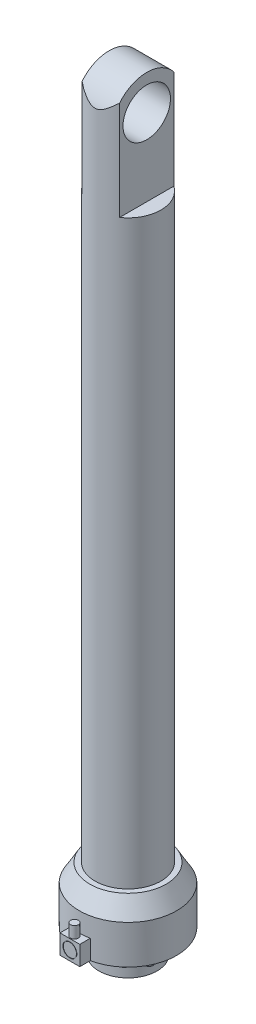
SolidWorks part; units mm, degrees
ref_plane "前基準面" through (0, 0, 0) normal (0, 0, 1) x (1, 0, 0)
ref_plane "上基準面" through (0, 0, 0) normal (0, 1, 0) x (1, 0, 0)
ref_plane "右基準面" through (0, 0, 0) normal (1, 0, 0) x (0, 0, -1)
sketch "草圖1" plane through (0, 0, 0) normal (0, 1, 0) x (1, 0, 0)
  circle A0 centre (0, 0) radius 8.5
  dimension "D1" = 17
extrude "填料-伸長1" add sketch "草圖1" along normal blind 150
sketch "草圖2" plane through (0, 150, 0) normal (0, 1, 0) x (1, 0, 0)
  line L1 (4.8323, -8.965) -> (-4.8323, -8.965)
  line L2 (4.8323, -8.965) -> (4.8323, 8.965)
  line L3 (4.8323, 8.965) -> (-4.8323, 8.965)
  line L4 (-4.8323, -8.965) -> (-4.8323, 8.965)
  line L5 (4.8323, -8.965) -> (-4.8323, 8.965) construction
  line L6 (4.8323, 8.965) -> (-4.8323, -8.965) construction
  point P0 (0, 0)
extrude "填料-伸長2" add sketch "草圖2" along normal blind 20
sketch "草圖3" plane through (4.8323, 0, 0) normal (1, 0, 0) x (0, 0, -1)
  line L0 (-8.965, 170) -> (8.965, 170) construction
  circle A0 centre (0, 170) radius 8.9308
extrude "填料-伸長3" add sketch "草圖3" against normal blind 9.7
sketch "草圖4" plane through (4.8323, 0, 0) normal (1, 0, 0) x (0, 0, -1)
  line L0 (0, -821.0692) -> (0, 49178.9308) construction
  line L1 (-1008.9308, 170) -> (48991.0692, 170) construction
  arc A0 (8.9308, 170) -> (-8.9308, 170) centre (0, 170) ccw construction
  circle A1 centre (0, 170) radius 6.1252
  point P6 (0, 178.9308)
extrude "除料-伸長1" cut sketch "草圖4" against normal blind 9.7
sketch "草圖5" plane through (0, 0, 0) normal (0, -1, 0) x (1, 0, 0)
  circle A0 centre (0, 0) radius 8.5
extrude "除料-伸長-薄件2" cut sketch "草圖5" against normal through all and the other way through all thin
sketch "草圖9" plane through (0, 0, 0) normal (1, 0, 0) x (0, 0, -1)
  line L0 (0, 0) -> (-9.8638, 0)
  line L1 (-9.8638, 0) -> (-12.56, -4.5997)
  line L2 (-12.56, -4.5997) -> (0, -4.5997)
  line L3 (0, -4.5997) -> (0, 0)
revolve "旋轉3" add sketch "草圖9" angle 360 about L3
sketch "草圖10" plane through (0, -4.5997, 0) normal (0, -1, 0) x (1, 0, 0)
  circle A0 centre (0, 0) radius 12.56
extrude "填料-伸長5" add sketch "草圖10" along normal blind 10
sketch "草圖11" plane through (0, -14.5997, 0) normal (0, -1, 0) x (1, 0, 0)
  line L0 (-1009.8752, 7.7611) -> (48990.1248, 7.7611) construction
  line L1 (-1011.7934, 4.3209) -> (48988.2066, 4.3209) construction
  line L2 (-1006.7311, -10.6041) -> (48993.2689, -10.6041) construction
  line L3 (-9.8752, 7.7611) -> (-7.1882, 7.7611) construction
  circle A0 centre (0, 0) radius 7.5
  circle A4 centre (-7.1882, 7.7611) radius 1
  circle A5 centre (0, 0) radius 12.56 construction
  circle A6 centre (-9.6928, 4.3209) radius 1
  circle A7 centre (6.7502, 7.7611) radius 1
  circle A8 centre (9.741, 4.3209) radius 1
  circle A9 centre (-3.1707, -10.6041) radius 1
  circle A10 centre (2.6052, -10.6041) radius 1
  dimension "D1" = 15
  dimension "D2" = 2
  dimension "D3" = 2
  dimension "D4" = 2
  dimension "D5" = 2
  dimension "D6" = 2
  dimension "D7" = 2
extrude "填料-伸長6" add sketch "草圖11" along normal blind 1
sketch "草圖12" plane through (0, -15.5997, 0) normal (0, -1, 0) x (1, 0, 0)
  circle A0 centre (0, 0) radius 7.5
extrude "填料-伸長7" add sketch "草圖12" along normal blind 5
ref_plane "平面1" through (0, 0, 13) normal (0, 0, 1) x (1, 0, 0)
sketch "草圖13" plane through (0, 0, 13) normal (0, 0, 1) x (1, 0, 0)
  line L0 (-12.56, -14.5997) -> (12.56, -14.5997) construction
  line L1 (2.56, -14.5997) -> (-2.56, -14.5997)
  line L2 (2.56, -14.5997) -> (2.56, -9.5997)
  line L3 (2.56, -9.5997) -> (-2.56, -9.5997)
  line L4 (-2.56, -14.5997) -> (-2.56, -9.5997)
  line L5 (2.56, -14.5997) -> (-2.56, -9.5997) construction
  line L6 (2.56, -9.5997) -> (-2.56, -14.5997) construction
  line L7 (12.56, -14.5997) -> (12.56, -4.5997) construction
  line L8 (-12.56, -4.5997) -> (-12.56, -14.5997) construction
  point P0 (0, -12.0997)
  dimension "D1" = 0
  dimension "D2" = 10
  dimension "D3" = 10
  dimension "D4" = 5
extrude "填料-伸長8" add sketch "草圖13" along normal blind 2 and the other way blind 1
sketch "草圖14" plane through (0, -9.5997, 0) normal (0, 1, 0) x (1, 0, 0)
  line L0 (0, -1015) -> (0, 48985) construction
  line L1 (2.56, -15) -> (-2.56, -15) construction
  circle A0 centre (0, -13.8) radius 1
  point P5 (0, -15)
  dimension "D1" = 2
  dimension "D2" = 1.2
extrude "填料-伸長9" add sketch "草圖14" along normal blind 3
sketch "草圖15" plane through (0, 0, 15) normal (0, 0, 1) x (1, 0, 0)
  circle A0 centre (0, -12.1221) radius 1.7062
extrude "除料-伸長-薄件3" cut sketch "草圖15" against normal blind 0.2 thin
sketch "草圖16" plane through (0, -20.5997, 0) normal (0, -1, 0) x (1, 0, 0)
  circle A0 centre (0, 0) radius 6
  dimension "D1" = 12
extrude "除料-伸長2" cut sketch "草圖16" against normal blind 130.2
